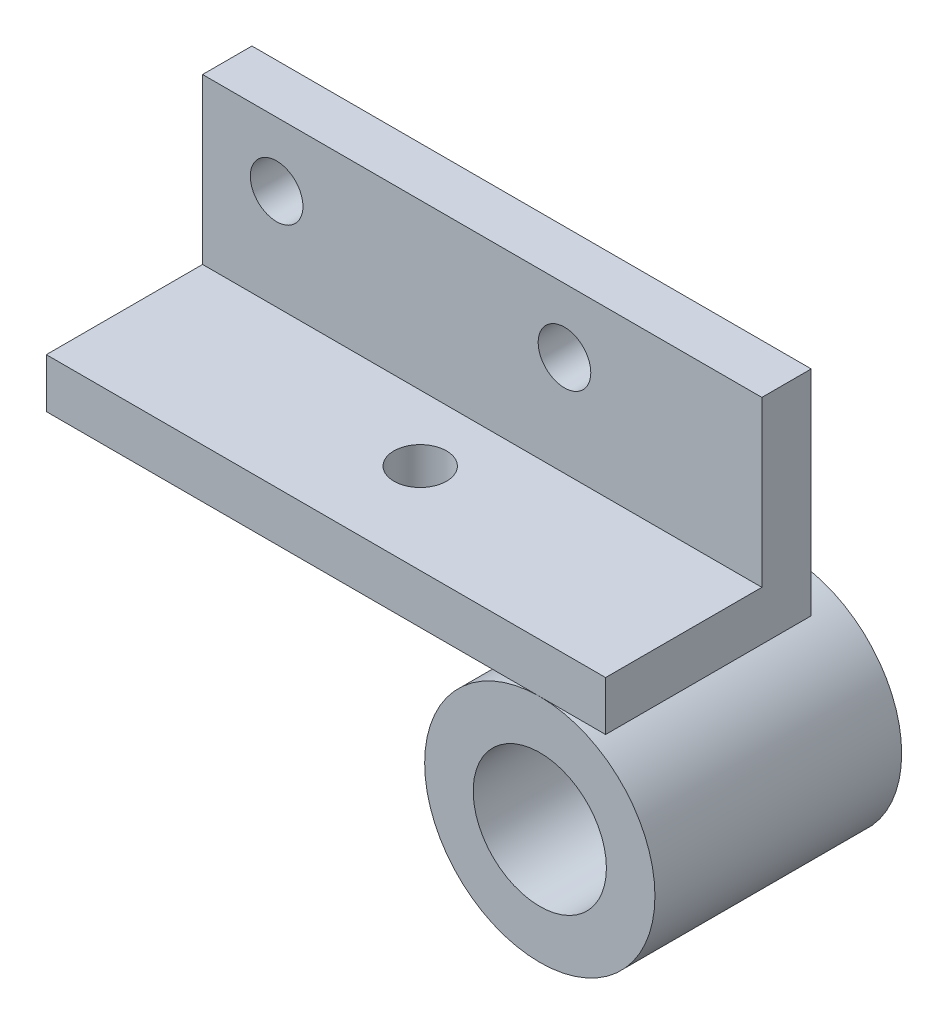
SolidWorks part; units mm, degrees
ref_plane "Alzado" through (0, 0, 0) normal (0, 0, 1) x (1, 0, 0)
ref_plane "Planta" through (0, 0, 0) normal (0, 1, 0) x (1, 0, 0)
ref_plane "Vista lateral" through (0, 0, 0) normal (1, 0, 0) x (0, 0, -1)
sketch "Croquis1" plane through (0, 0, 0) normal (0, 1, 0) x (1, 0, 0)
  line L1 (0, 0) -> (34, 0)
  line L2 (0, 0) -> (0, 9.5)
  line L3 (0, 9.5) -> (34, 9.5)
  line L4 (34, 0) -> (34, 9.5)
  dimension "D1" = 9.5
  dimension "D2" = 34
extrude "Saliente-Extruir1" add sketch "Croquis1" along normal blind 3
sketch "Croquis2" plane through (0, 0, 0) normal (0, -1, 0) x (1, 0, 0)
  line L0 (34, 0) -> (34, -9.5) construction
  line L1 (0, -9.5) -> (34, -9.5)
  line L2 (0, -9.5) -> (0, -12.5)
  line L3 (0, -12.5) -> (34, -12.5)
  line L4 (34, -9.5) -> (34, -12.5)
  line L5 (34, -9.5) -> (0, -9.5) construction
  point P5 (34, -9.5)
  dimension "D1" = 3
extrude "Saliente-Extruir2" add sketch "Croquis2" against normal blind 13
sketch "Croquis3" plane through (0, 0, -12.5) normal (0, 0, -1) x (-1, 0, 0)
  line L0 (0, 0) -> (-34, 0) construction
  line L1 (-34, 13) -> (-34, 0) construction
  circle A0 centre (-4.5, 9.1) radius 1.6
  circle A1 centre (-22, 9.1) radius 1.6
  point P4 (0, 0)
  point P5 (0, 0)
  dimension "D1" = 3.2
  dimension "D2" = 17.5
  dimension "D3" = 9.1
  dimension "D4" = 12
extrude "Cortar-Extruir1" cut sketch "Croquis3" against normal up to surface (3 mm away) up to face at (17, 8, -9.5)
sketch "Croquis4" plane through (0, 0, 0) normal (0, -1, 0) x (1, 0, 0)
  line L0 (0, 0) -> (34, 0) construction
  line L1 (34, 0) -> (34, -12.5) construction
  circle A0 centre (17.23, -5.5) radius 1.6
  dimension "D1" = 3.2
  dimension "D2" = 5.5
  dimension "D3" = 16.77
extrude "Cortar-Extruir2" cut sketch "Croquis4" against normal up to surface (3 mm away) up to face at (17, 3, -4.75)
sketch "Croquis5" plane through (0, 0, 0) normal (0, 0, 1) x (1, 0, 0)
  line L0 (0, 0) -> (34, 0) construction
  line L1 (0, 3) -> (0, 0) construction
  circle A0 centre (30, -7) radius 7
  point P2 (29.0265, -7.3739)
  dimension "D1" = 14
  dimension "D2" = 30
extrude "Saliente-Extruir3" add sketch "Croquis5" against normal blind 15 separate body
sketch "Croquis6" plane through (0, 0, 0) normal (0, 0, 1) x (1, 0, 0)
  circle A0 centre (30, -7) radius 4.05
  dimension "D1" = 8.1
extrude "Cortar-Extruir3" cut sketch "Croquis6" against normal through all
